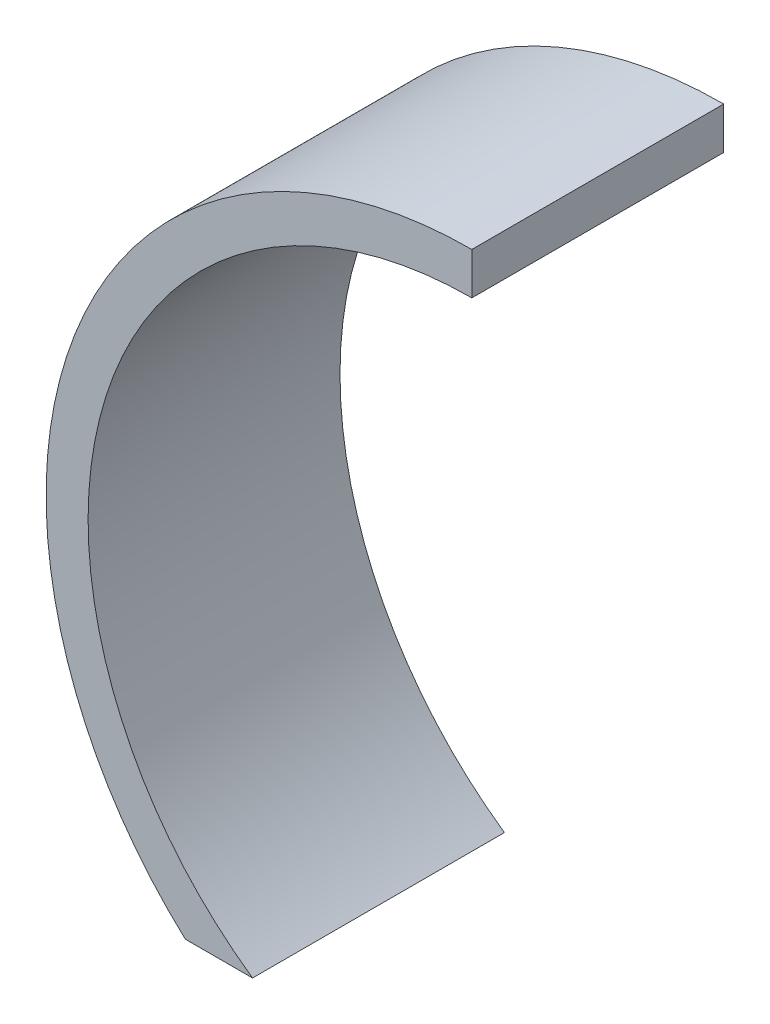
SolidWorks part; units mm, degrees
ref_plane "Front Plane" through (0, 0, 0) normal (0, 0, 1) x (1, 0, 0)
ref_plane "Top Plane" through (0, 0, 0) normal (0, 1, 0) x (1, 0, 0)
ref_plane "Right Plane" through (0, 0, 0) normal (1, 0, 0) x (0, 0, -1)
sketch "Sketch1" plane through (0, 0, 0) normal (0, 0, 1) x (1, 0, 0)
  line L0 (0, 58.04) -> (0, 64.39)
  line L1 (-36.7994, -52.8382) -> (-33.1703, -47.6274)
  arc A0 (0, 58.04) -> (-33.1703, -47.6274) centre (0, 0) ccw
  arc A1 (0, 64.39) -> (-36.7994, -52.8382) centre (0, 0) ccw
  circle A3 centre (0, 0) radius 55.5 construction
  dimension "D2" = 2.54
  dimension "D3" = 111
  dimension "D1" = 6.35
extrude "Boss-Extrude1" add sketch "Sketch1" against normal up to surface (38.1 mm away) contours A1 L1 A0 L0
sketch "Sketch2" plane through (0, 0, 0) normal (0, 0, 1) x (1, 0, 0)
  line L0 (-33.1703, -47.6274) -> (-43.3324, -47.6274)
  line L1 (-101.288, -47.6274) -> (-33.1703, -47.6274) construction
  line L3 (-36.7994, -52.8382) -> (-33.1703, -47.6274)
  arc A0 (0, 64.39) -> (-36.7994, -52.8382) centre (0, 0) ccw construction
  arc A1 (-36.7994, -52.8382) -> (-43.3324, -47.6274) centre (0, 0) cw
  arc M2 (0, 64.39) -> (-36.7994, -52.8382) centre (0, 0) ccw
  line M3 (-36.7994, -52.8382) -> (-33.1703, -47.6274)
extrude "Cut-Extrude1" cut sketch "Sketch2" against normal through all contours L0 M3 M2
